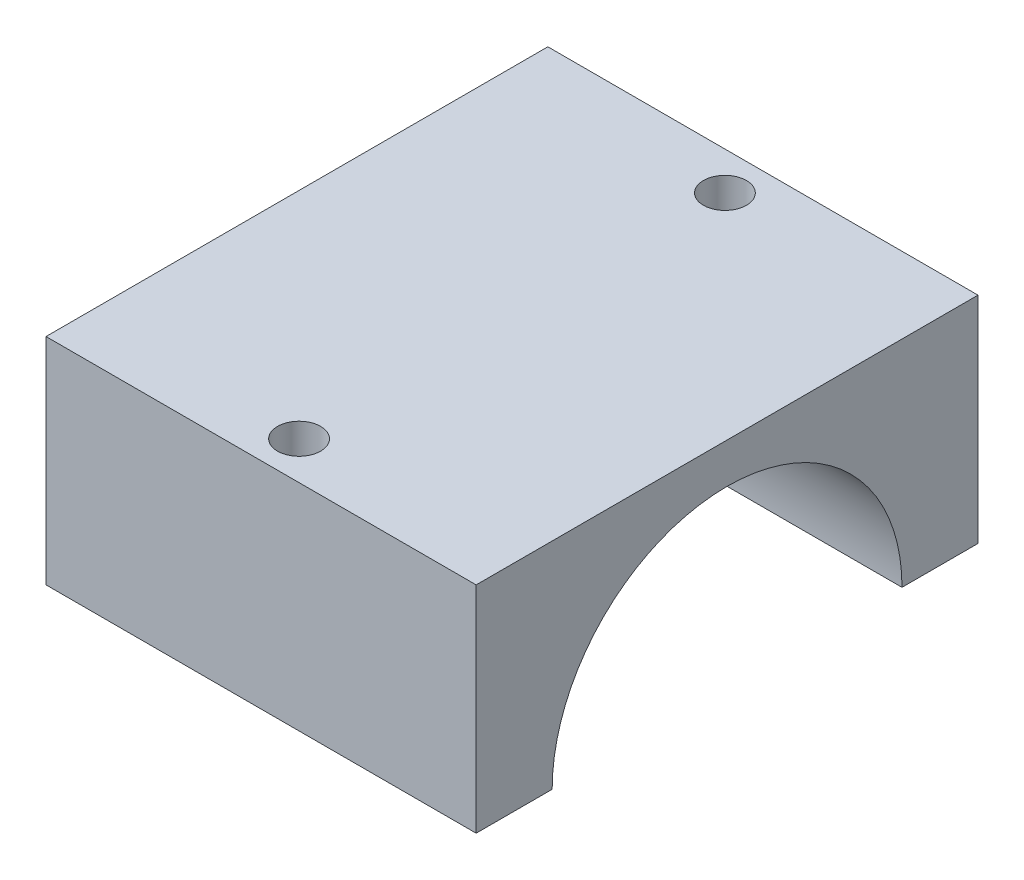
SolidWorks part; units mm, degrees
ref_plane "Front Plane" through (0, 0, 0) normal (0, 0, 1) x (1, 0, 0)
ref_plane "Top Plane" through (0, 0, 0) normal (0, 1, 0) x (1, 0, 0)
ref_plane "Right Plane" through (0, 0, 0) normal (1, 0, 0) x (0, 0, -1)
sketch "Sketch1" plane through (0, 0, 0) normal (1, 0, 0) x (0, 0, -1)
  line L0 (-17.5, 0) -> (-17.5, 15)
  line L1 (-17.5, 15) -> (17.5, 15)
  line L2 (17.5, 15) -> (17.5, 0)
  line L3 (17.5, 0) -> (12.2, 0)
  line L4 (-12.2, 0) -> (-17.5, 0)
  arc A0 (12.2, 0) -> (-12.2, 0) centre (0, 0) ccw
  point P8 (0, 0)
  point P9 (0, 15)
  point P10 (30.3409, 32.109)
  point P11 (16.7077, 15)
  dimension "D1" = 24.4
  dimension "D2" = 15
  dimension "D3" = 35
extrude "Boss-Extrude1" add sketch "Sketch1" along normal blind 30
sketch "Sketch2" plane through (0, 15, 0) normal (0, 1, 0) x (1, 0, 0)
  line L1 (0, -17.5) -> (0, -12.2) construction
  line L2 (30, -17.5) -> (0, -17.5) construction
  line L3 (0, 12.2) -> (0, 17.5) construction
  line L4 (30, 17.5) -> (0, 17.5) construction
  point P0 (15, -14.85)
  point P1 (15, 14.85)
  point P2 (0, 0)
  point P3 (0, 0)
  point P7 (0, -14.85)
  point P9 (15, -17.5)
  point P10 (0, 0)
  point P13 (0, 14.85)
  point P16 (0, 0)
  point P17 (15, 17.5)
hole_wizard "Ø3.0mm Dowel Hole1" positions "3DSketch1" profile "Sketch3" hole size "Ø3.0" standard "ANSI Metric" end condition through all
sketch3d "3DSketch1"
  point P0 (15, 15, -14.85)
  point P3 (15, 15, 14.85)
sketch "Sketch3" plane through (15, 15, -14.85) normal (1, 0, 0) x (0, 0, 1)
  line L0 (0, 0) -> (0, 15)
  line L1 (0, 15) -> (1.5, 15)
  line L2 (1.5, 15) -> (1.5, 0)
  line L5 (1.5, 0) -> (0, 0)
  line L11 (0, -6.35) -> (0, 107.95) construction
  dimension "Thru Hole Dia." = 3
  dimension "Thru Hole Depth" = 15
